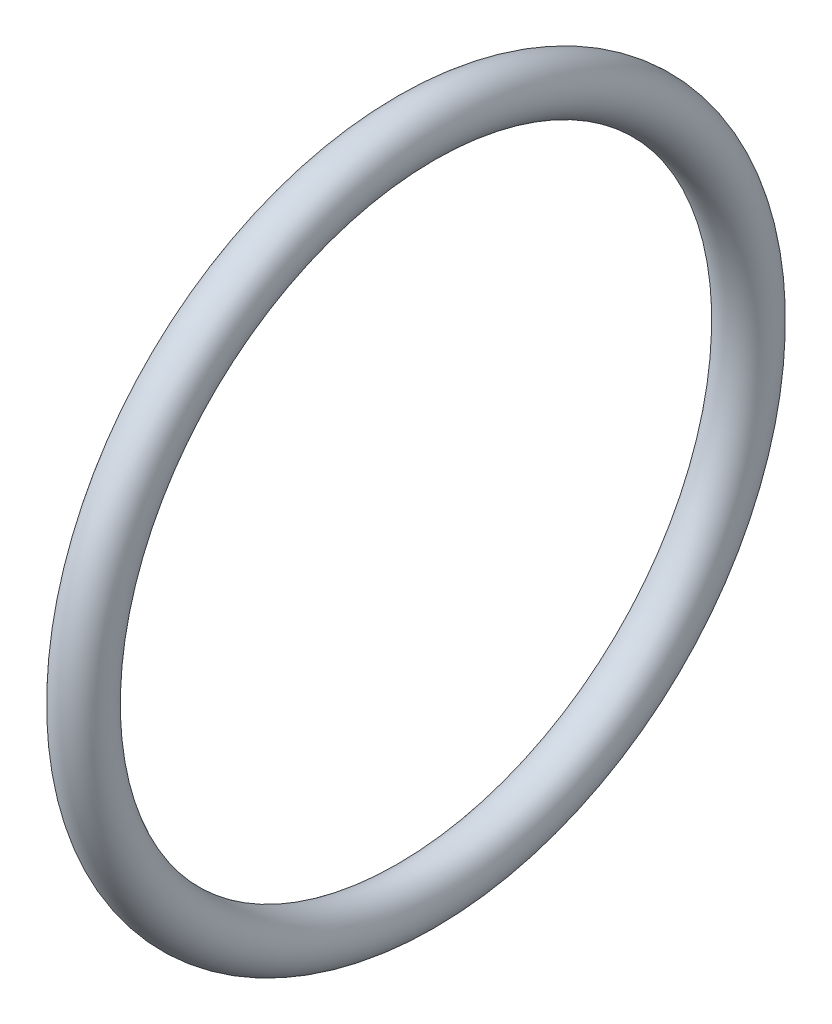
SolidWorks part; units mm, degrees
ref_plane "Спереди" through (0, 0, 0) normal (0, 0, 1) x (1, 0, 0)
ref_plane "Сверху" through (0, 0, 0) normal (0, 1, 0) x (1, 0, 0)
ref_plane "Справа" through (0, 0, 0) normal (1, 0, 0) x (0, 0, -1)
sketch "Эскиз1" plane through (0, 0, 0) normal (0, 0, 1) x (1, 0, 0)
  line L0 (0, 0) -> (-37.9546, 0) construction
  circle A0 centre (0, 25.5) radius 2
  point P5 (0, 0)
  dimension "D1" = 4
  dimension "D2" = 25.5
revolve "Повернуть1" add sketch "Эскиз1" angle 360 about L0
